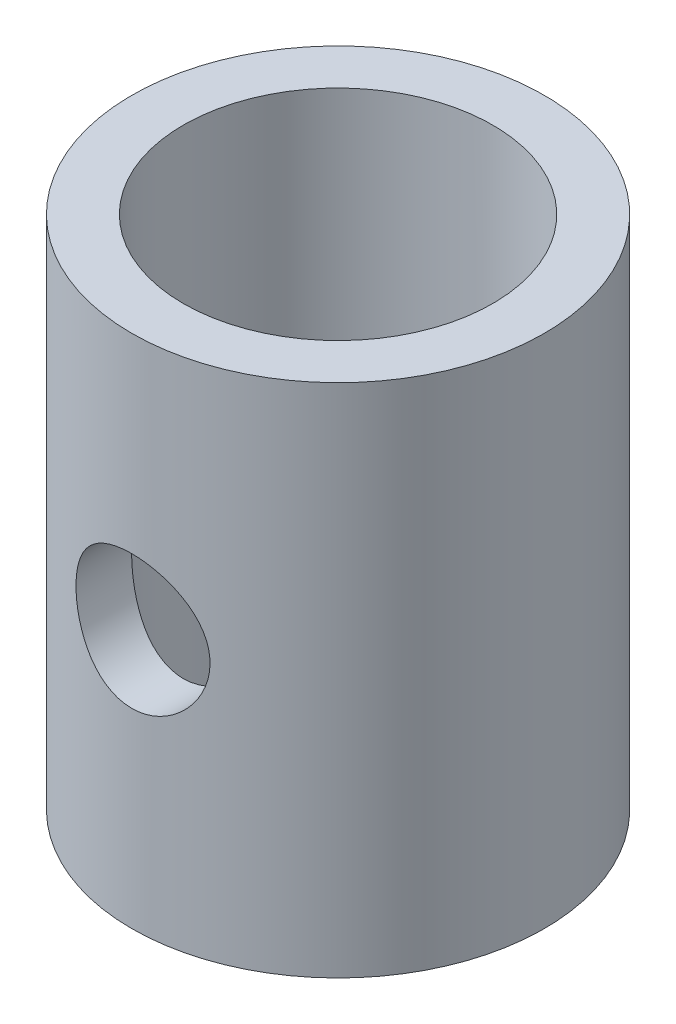
SolidWorks part; units mm, degrees
ref_plane "Front Plane" through (0, 0, 0) normal (0, 0, 1) x (1, 0, 0)
ref_plane "Top Plane" through (0, 0, 0) normal (0, 1, 0) x (1, 0, 0)
ref_plane "Right Plane" through (0, 0, 0) normal (1, 0, 0) x (0, 0, -1)
sketch "Sketch1" plane through (0, 0, 0) normal (0, 1, 0) x (1, 0, 0)
  circle A0 centre (0, 0) radius 2
extrude "Boss-Extrude1" add sketch "Sketch1" along normal blind 5
sketch "Sketch2" plane through (0, 5, 0) normal (0, 1, 0) x (1, 0, 0)
  circle A0 centre (0, 0) radius 1.5
extrude "Cut-Extrude1" cut sketch "Sketch2" against normal through all
sketch "Sketch5" plane through (0, 0, 0) normal (0, 0, 1) x (1, 0, 0)
  line L0 (-2, 2.5) -> (2, 2.5) construction
  line L1 (-2, 5) -> (-2, 0) construction
  line L2 (2, 0) -> (2, 5) construction
  line L3 (0, 0) -> (0, 5) construction
  line L4 (1.5, 5) -> (-1.5, 5) construction
  circle A0 centre (0, 2.5) radius 0.65
extrude "Cut-Extrude4" cut sketch "Sketch5" against normal through all both and the other way through all
